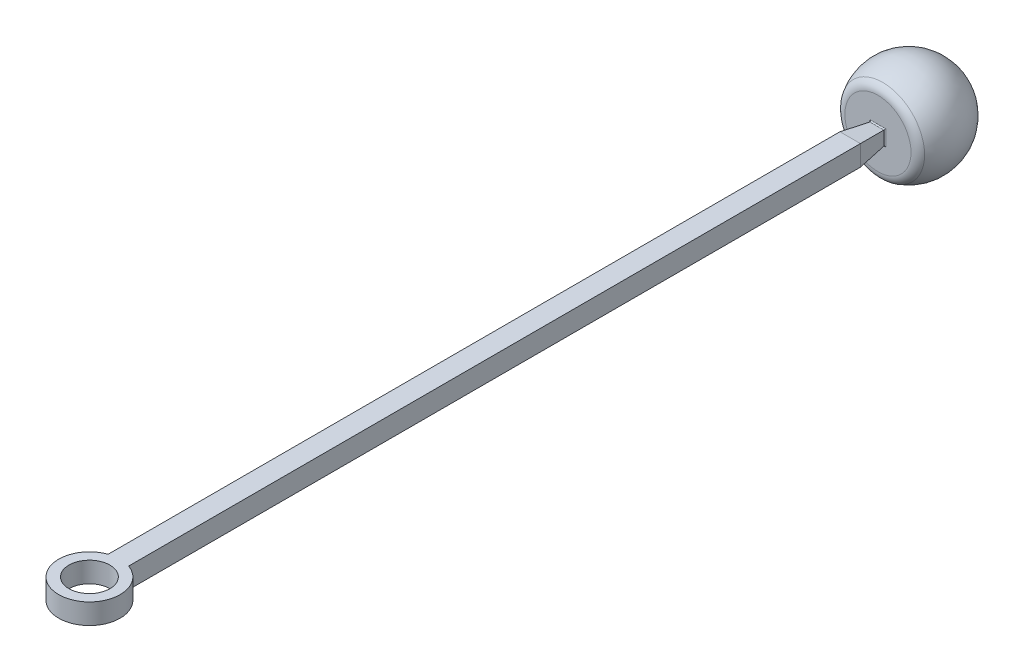
SolidWorks part; units mm, degrees
ref_plane "Front Plane" through (0, 0, 0) normal (0, 0, 1) x (1, 0, 0)
ref_plane "Top Plane" through (0, 0, 0) normal (0, 1, 0) x (1, 0, 0)
ref_plane "Right Plane" through (0, 0, 0) normal (1, 0, 0) x (0, 0, -1)
sketch "Sketch1" plane through (0, 0, 0) normal (0, 0, 1) x (1, 0, 0)
  line L0 (0, 24) -> (0, -24)
  arc A0 (0, 24) -> (0, -24) centre (0, 0) cw
  dimension "D1" = 48
revolve "Revolve1" add sketch "Sketch1" angle 360 about L0
sketch "Sketch2" plane through (0, 0, 0) normal (0, 0, 1) x (1, 0, 0)
  line L1 (-5, -5) -> (5, -5)
  line L2 (-5, -5) -> (-5, 5)
  line L3 (-5, 5) -> (5, 5)
  line L4 (5, -5) -> (5, 5)
  line L5 (-5, -5) -> (5, 5) construction
  line L6 (-5, 5) -> (5, -5) construction
  point P0 (0, 0)
  dimension "D1" = 10
extrude "Boss-Extrude1" add sketch "Sketch2" along normal blind 400
sketch "Sketch3" plane through (0, 5, 0) normal (0, 1, 0) x (1, 0, 0)
  line L0 (5, -400) -> (-5, -400) construction
  circle A0 centre (0, -400) radius 15
  dimension "D1" = 30
extrude "Boss-Extrude2" add sketch "Sketch3" against normal up to surface (10 mm away) up to face at (0, -5, 211.602)
sketch "Sketch4" plane through (0, 5, 0) normal (0, 1, 0) x (1, 0, 0)
  circle A0 centre (0, -400) radius 10
  dimension "D1" = 20
extrude "Cut-Extrude1" cut sketch "Sketch4" against normal up to surface (10 mm away) up to face at (0, -5, 211.8165)
sketch "Sketch5" plane through (0, 0, 0) normal (0, 0, 1) x (1, 0, 0)
  line L9 (-3.335, -3.335) -> (3.335, -3.335)
  line L10 (-3.335, -3.335) -> (-3.335, 3.335)
  line L11 (-3.335, 3.335) -> (3.335, 3.335)
  line L12 (3.335, -3.335) -> (3.335, 3.335)
  line L13 (-3.335, -3.335) -> (3.335, 3.335) construction
  line L14 (-3.335, 3.335) -> (3.335, -3.335) construction
  point P3 (0, 0)
  dimension "D1" = 6.67
  dimension "D2" = 6.67
extrude "Cut-Extrude2" cut sketch "Sketch5" along normal blind 400 draft 7 from offset 15 flip side to cut
fillet "Fillet1" radius 0.5 4 edges at (3.335, 0, 15) (0, -3.335, 15) (-3.335, 0, 15) (0, 3.335, 15)
fillet "Fillet2" radius 5 1 edges at (18.735, 0, 15)
